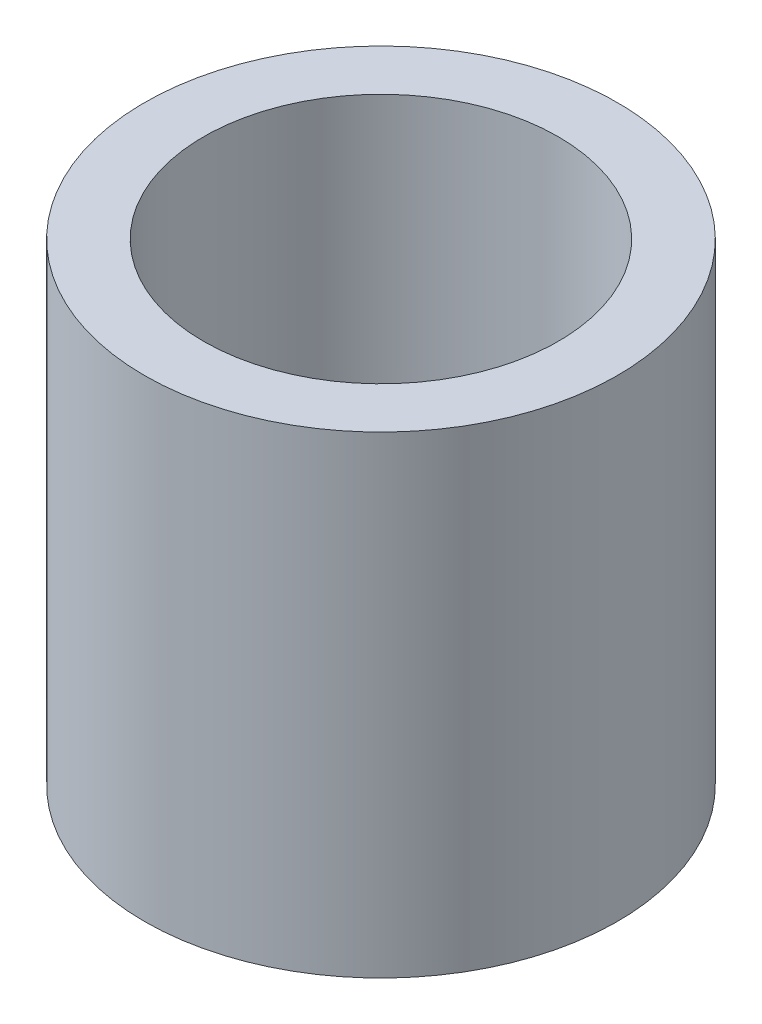
SolidWorks part; units mm, degrees
ref_plane "Front Plane" through (0, 0, 0) normal (0, 0, 1) x (1, 0, 0)
ref_plane "Top Plane" through (0, 0, 0) normal (0, 1, 0) x (1, 0, 0)
ref_plane "Right Plane" through (0, 0, 0) normal (1, 0, 0) x (0, 0, -1)
sketch "Sketch1" plane through (0, 0, 0) normal (0, 1, 0) x (1, 0, 0)
  circle A0 centre (0, 0) radius 8
  circle A1 centre (0, 0) radius 6
  dimension "D1" = 12
  dimension "D2" = 16
extrude "Boss-Extrude1" add sketch "Sketch1" along normal blind 16
